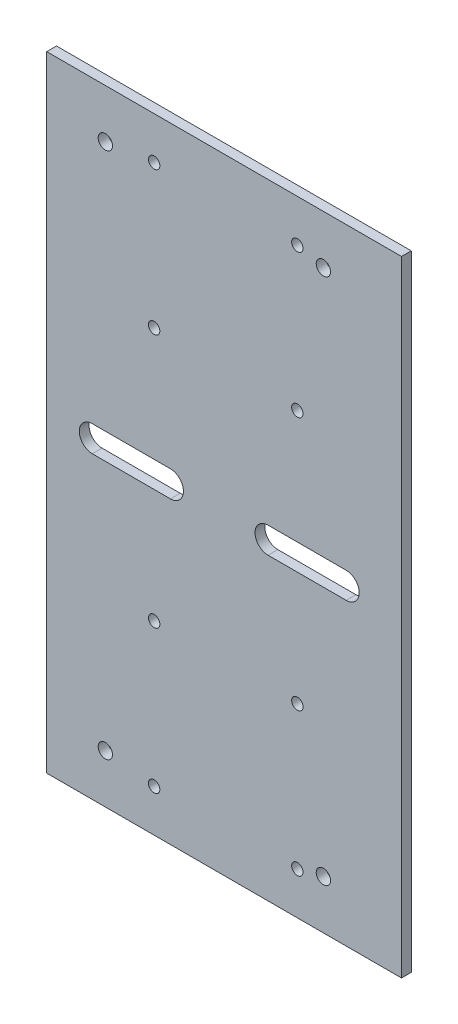
SolidWorks part; units mm, degrees
ref_plane "Front Plane" through (0, 0, 0) normal (0, 0, 1) x (1, 0, 0)
ref_plane "Top Plane" through (0, 0, 0) normal (0, 1, 0) x (1, 0, 0)
ref_plane "Right Plane" through (0, 0, 0) normal (1, 0, 0) x (0, 0, -1)
sketch "Wiring slots and deck mounts profile" plane through (0, 0, 0) normal (0, 0, 1) x (1, 0, 0)
  line L0 (-55, -96) -> (54, -96)
  line L1 (54, -96) -> (54, 96)
  line L2 (54, 96) -> (-55, 96)
  line L3 (-55, 96) -> (-55, -96)
  line L4 (-41, -4) -> (-17, -4)
  line L5 (-17, 4) -> (-41, 4)
  line L6 (13, -4) -> (37, -4)
  line L7 (37, 4) -> (13, 4)
  circle A0 centre (-37, -81) radius 2.2
  circle A1 centre (-37, 81) radius 2.2
  circle A2 centre (30, -81) radius 2.2
  circle A3 centre (30, 81) radius 2.2
  circle A4 centre (-22, -83) radius 1.75
  circle A5 centre (-22, 39) radius 1.75
  circle A6 centre (-22, -39) radius 1.75
  circle A7 centre (-22, 83) radius 1.75
  circle A8 centre (22, -83) radius 1.75
  circle A9 centre (22, 39) radius 1.75
  circle A10 centre (22, -39) radius 1.75
  circle A11 centre (22, 83) radius 1.75
  arc A12 (-17, -4) -> (-17, 4) centre (-17, 0) ccw
  arc A13 (-41, 4) -> (-41, -4) centre (-41, 0) ccw
  arc A14 (37, -4) -> (37, 4) centre (37, 0) ccw
  arc A15 (13, 4) -> (13, -4) centre (13, 0) ccw
extrude "Wiring slots and deck mounts" add sketch "Wiring slots and deck mounts profile" along normal blind 3
